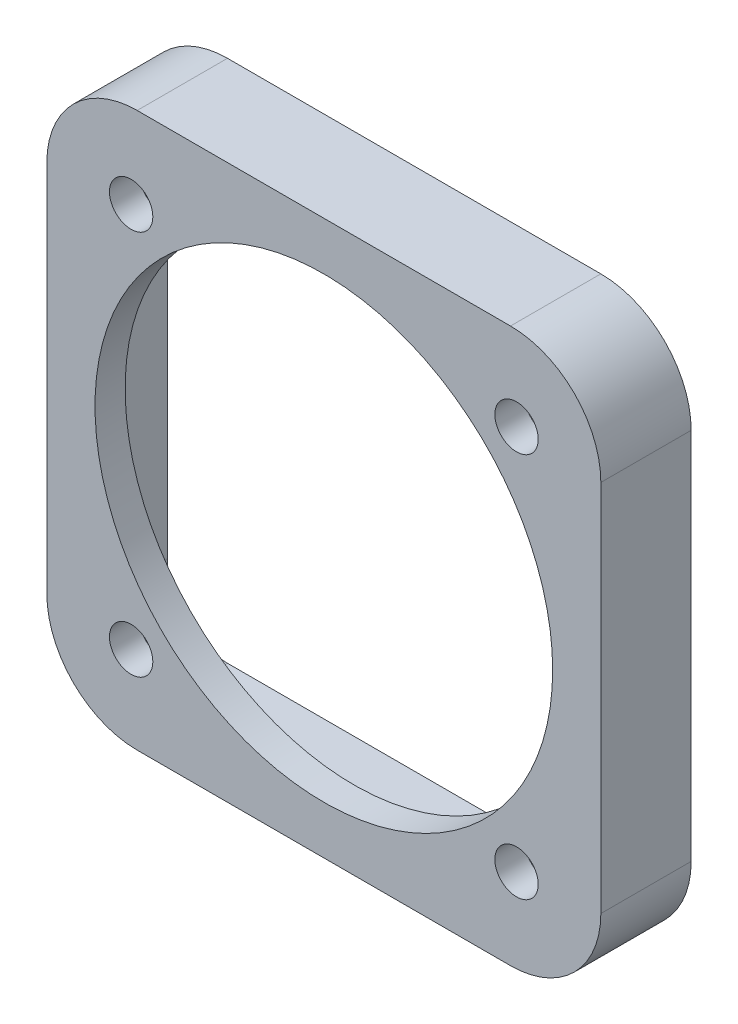
SolidWorks part; units mm, degrees
material "Custom Plastic"
ref_plane "X-Y Datum" through (0, 0, 0) normal (0, 0, 1) x (1, 0, 0)
ref_plane "X-Z Datum" through (0, 0, 0) normal (0, 1, 0) x (1, 0, 0)
ref_plane "Y-Z Datum" through (0, 0, 0) normal (1, 0, 0) x (0, 0, -1)
sketch "Sketch2" plane through (0, 0, -2000) normal (0, 0, 1) x (1, 0, 0)
  line L0 (98.399, 128.0859) -> (98.399, 159.0859) construction
  line L1 (133.899, 123.5859) -> (102.899, 123.5859) construction
  line L2 (138.399, 131.3331) -> (138.399, 128.0859) construction
  line L3 (138.399, 133.0859) -> (138.399, 131.3331) construction
  line L4 (138.399, 133.0859) -> (138.399, 133.3859) construction
  line L5 (138.399, 135.3859) -> (138.399, 135.6859) construction
  line L6 (138.399, 138.7859) -> (138.399, 135.6859) construction
  line L7 (138.399, 159.0859) -> (138.399, 138.7859) construction
  line L8 (102.899, 163.5859) -> (133.899, 163.5859) construction
  line L9 (98.399, 128.0859) -> (98.399, 159.0859) construction
  line L10 (133.899, 123.5859) -> (102.899, 123.5859) construction
  line L11 (138.399, 131.3331) -> (138.399, 128.0859) construction
  line L12 (138.399, 133.0859) -> (138.399, 131.3331) construction
  line L13 (138.399, 133.0859) -> (138.399, 133.3859) construction
  line L14 (138.399, 135.3859) -> (138.399, 135.6859) construction
  line L15 (138.399, 138.7859) -> (138.399, 135.6859) construction
  line L16 (138.399, 159.0859) -> (138.399, 138.7859) construction
  line L17 (102.899, 163.5859) -> (133.899, 163.5859) construction
  line L18 (138.399, 135.3859) -> (138.399, 133.3859) construction
  line L19 (138.899, 138.7859) -> (138.899, 135.6859)
  line L20 (138.899, 135.3859) -> (138.899, 135.6859)
  line L21 (138.899, 135.3859) -> (138.899, 133.3859)
  line L22 (138.899, 133.0859) -> (138.899, 133.3859)
  line L23 (138.899, 133.0859) -> (138.899, 131.3331)
  line L24 (138.899, 131.3331) -> (138.899, 128.0859)
  line L25 (133.899, 123.0859) -> (102.899, 123.0859)
  line L26 (97.899, 128.0859) -> (97.899, 159.0859)
  line L27 (102.899, 164.0859) -> (133.899, 164.0859)
  line L28 (138.899, 159.0859) -> (138.899, 138.7859)
  line L29 (102.899, 166.5859) -> (133.899, 166.5859)
  line L30 (141.399, 159.0859) -> (141.399, 138.7859)
  line L31 (141.399, 138.7859) -> (141.399, 135.6859)
  line L32 (141.399, 135.3859) -> (141.399, 135.6859)
  line L33 (141.399, 135.3859) -> (141.399, 133.3859)
  line L34 (141.399, 133.0859) -> (141.399, 133.3859)
  line L35 (141.399, 133.0859) -> (141.399, 131.3331)
  line L36 (141.399, 131.3331) -> (141.399, 128.0859)
  line L37 (133.899, 120.5859) -> (102.899, 120.5859)
  line L38 (95.399, 128.0859) -> (95.399, 159.0859)
  arc A0 (132.349, 159.5859) -> (136.449, 159.5859) centre (134.399, 159.5859) ccw construction
  arc A1 (136.449, 159.5859) -> (132.349, 159.5859) centre (134.399, 159.5859) ccw construction
  arc A2 (132.349, 127.5859) -> (136.449, 127.5859) centre (134.399, 127.5859) ccw construction
  arc A3 (136.449, 127.5859) -> (132.349, 127.5859) centre (134.399, 127.5859) ccw construction
  arc A4 (100.349, 127.5859) -> (104.449, 127.5859) centre (102.399, 127.5859) ccw construction
  arc A5 (104.449, 127.5859) -> (100.349, 127.5859) centre (102.399, 127.5859) ccw construction
  arc A6 (100.349, 159.5859) -> (104.449, 159.5859) centre (102.399, 159.5859) ccw construction
  arc A7 (104.449, 159.5859) -> (100.349, 159.5859) centre (102.399, 159.5859) ccw construction
  arc A8 (98.399, 128.0859) -> (102.899, 123.5859) centre (102.899, 128.0859) ccw construction
  arc A9 (133.899, 123.5859) -> (138.399, 128.0859) centre (133.899, 128.0859) ccw construction
  arc A10 (138.399, 159.0859) -> (133.899, 163.5859) centre (133.899, 159.0859) ccw construction
  arc A11 (102.899, 163.5859) -> (98.399, 159.0859) centre (102.899, 159.0859) ccw construction
  arc A12 (132.349, 159.5859) -> (136.449, 159.5859) centre (134.399, 159.5859) ccw construction
  arc A13 (136.449, 159.5859) -> (132.349, 159.5859) centre (134.399, 159.5859) ccw construction
  arc A14 (132.349, 127.5859) -> (136.449, 127.5859) centre (134.399, 127.5859) ccw construction
  arc A15 (136.449, 127.5859) -> (132.349, 127.5859) centre (134.399, 127.5859) ccw construction
  arc A16 (100.349, 127.5859) -> (104.449, 127.5859) centre (102.399, 127.5859) ccw construction
  arc A17 (104.449, 127.5859) -> (100.349, 127.5859) centre (102.399, 127.5859) ccw construction
  arc A18 (100.349, 159.5859) -> (104.449, 159.5859) centre (102.399, 159.5859) ccw construction
  arc A19 (104.449, 159.5859) -> (100.349, 159.5859) centre (102.399, 159.5859) ccw construction
  arc A20 (98.399, 128.0859) -> (102.899, 123.5859) centre (102.899, 128.0859) ccw construction
  arc A21 (133.899, 123.5859) -> (138.399, 128.0859) centre (133.899, 128.0859) ccw construction
  arc A22 (138.399, 159.0859) -> (133.899, 163.5859) centre (133.899, 159.0859) ccw construction
  arc A23 (102.899, 163.5859) -> (98.399, 159.0859) centre (102.899, 159.0859) ccw construction
  arc A24 (133.899, 123.0859) -> (138.899, 128.0859) centre (133.899, 128.0859) ccw
  arc A25 (97.899, 128.0859) -> (102.899, 123.0859) centre (102.899, 128.0859) ccw
  arc A26 (102.899, 164.0859) -> (97.899, 159.0859) centre (102.899, 159.0859) ccw
  arc A27 (138.899, 159.0859) -> (133.899, 164.0859) centre (133.899, 159.0859) ccw
  arc A28 (141.399, 159.0859) -> (133.899, 166.5859) centre (133.899, 159.0859) ccw
  arc A29 (133.899, 120.5859) -> (141.399, 128.0859) centre (133.899, 128.0859) ccw
  arc A30 (95.399, 128.0859) -> (102.899, 120.5859) centre (102.899, 128.0859) ccw
  arc A31 (102.899, 166.5859) -> (95.399, 159.0859) centre (102.899, 159.0859) ccw
  arc A32 (99.4131, 142.8523) -> (99.4603, 142.0609) centre (118.399, 143.5859) ccw construction
  arc A33 (99.4603, 142.0609) -> (102.1845, 133.6818) centre (118.399, 143.5859) ccw construction
  arc A34 (105.3986, 157.442) -> (100.5461, 150.0878) centre (118.399, 143.5859) ccw construction
  arc A35 (99.4131, 142.8523) -> (99.4603, 142.0609) centre (118.399, 143.5859) ccw
  arc A36 (99.4603, 142.0609) -> (102.1845, 133.6818) centre (118.399, 143.5859) ccw
  arc A37 (105.3986, 157.442) -> (100.5461, 150.0878) centre (118.399, 143.5859) ccw
  circle A38 centre (118.399, 143.5859) radius 19
  dimension "D1" = 0.5
  dimension "D2" = 2.5
extrude "Boss-Extrude2" add sketch "Sketch2" along normal blind 2.5 contours L29 A31 L38 A30 L37 A29 L36 L35 L34 L33 L32 L31 L30 A28 A27 L28 L19 L20 L21 L22 L23 L24 A24 L25 A25 L26 A26 L27 | L28 A27 L27 A26 L26 A25 L25 A24 L24 L23 L22 L21 L20 L19 A38 A37 A36 A35
sketch "Sketch4" plane through (0, 0, -2000) normal (0, 0, -1) x (-1, 0, 0)
  line L0 (-102.899, 164.0859) -> (-133.899, 164.0859)
  line L1 (-138.899, 159.0859) -> (-138.899, 128.0859)
  line L2 (-133.899, 123.0859) -> (-102.899, 123.0859)
  line L3 (-97.899, 128.0859) -> (-97.899, 159.0859)
  line L4 (-102.899, 166.5859) -> (-133.899, 166.5859)
  line L5 (-141.399, 159.0859) -> (-141.399, 128.0859)
  line L6 (-133.899, 120.5859) -> (-102.899, 120.5859)
  line L7 (-95.399, 128.0859) -> (-95.399, 159.0859)
  line L8 (-102.899, 166.5859) -> (-133.899, 166.5859)
  line L9 (-141.399, 159.0859) -> (-141.399, 128.0859)
  line L10 (-133.899, 120.5859) -> (-102.899, 120.5859)
  line L11 (-95.399, 128.0859) -> (-95.399, 159.0859)
  arc A0 (-133.899, 164.0859) -> (-138.899, 159.0859) centre (-133.899, 159.0859) ccw
  arc A1 (-138.899, 128.0859) -> (-133.899, 123.0859) centre (-133.899, 128.0859) ccw
  arc A2 (-102.899, 123.0859) -> (-97.899, 128.0859) centre (-102.899, 128.0859) ccw
  arc A3 (-97.899, 159.0859) -> (-102.899, 164.0859) centre (-102.899, 159.0859) ccw
  arc A4 (-133.899, 166.5859) -> (-141.399, 159.0859) centre (-133.899, 159.0859) ccw
  arc A5 (-141.399, 128.0859) -> (-133.899, 120.5859) centre (-133.899, 128.0859) ccw
  arc A6 (-102.899, 120.5859) -> (-95.399, 128.0859) centre (-102.899, 128.0859) ccw
  arc A7 (-95.399, 159.0859) -> (-102.899, 166.5859) centre (-102.899, 159.0859) ccw
  arc A8 (-133.899, 166.5859) -> (-141.399, 159.0859) centre (-133.899, 159.0859) ccw
  arc A9 (-141.399, 128.0859) -> (-133.899, 120.5859) centre (-133.899, 128.0859) ccw
  arc A10 (-102.899, 120.5859) -> (-95.399, 128.0859) centre (-102.899, 128.0859) ccw
  arc A11 (-95.399, 159.0859) -> (-102.899, 166.5859) centre (-102.899, 159.0859) ccw
  dimension "D1" = 0
  dimension "D2" = 2.5
extrude "Boss-Extrude3" add sketch "Sketch4" along normal blind 5
hole_wizard "M3 Clearance Hole1" positions "Sketch9" profile "Sketch8" hole size "M3" standard "ANSI Metric" end condition up to next
sketch "Sketch9" plane through (0, 0, -1997.5) normal (0, 0, 1) x (1, 0, 0)
  point P0 (102.399, 159.5859)
  point P3 (102.399, 127.5859)
  point P6 (134.399, 127.5859)
  point P9 (134.399, 159.5859)
sketch "Sketch8" plane through (102.399, 159.5859, -1997.5) normal (1, 0, 0) x (0, -1, 0)
  line L0 (0, 0) -> (0, 2.5)
  line L1 (0, 2.5) -> (1.8, 2.5)
  line L2 (1.8, 2.5) -> (1.8, 0)
  line L5 (1.8, 0) -> (0, 0)
  line L11 (0, -6.35) -> (0, 107.95) construction
  dimension "Thru Hole Dia." = 3.6
  dimension "Thru Hole Depth" = 2.5
